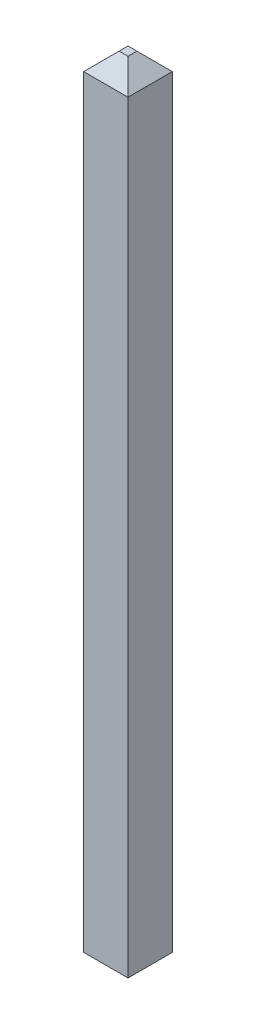
SolidWorks part; units mm, degrees
ref_plane "Front Plane" through (0, 0, 0) normal (0, 0, 1) x (1, 0, 0)
ref_plane "Top Plane" through (0, 0, 0) normal (0, 1, 0) x (1, 0, 0)
ref_plane "Right Plane" through (0, 0, 0) normal (1, 0, 0) x (0, 0, -1)
sketch "Sketch1" plane through (0, 0, 0) normal (0, 1, 0) x (1, 0, 0)
  line L0 (-0.3175, 0.3175) -> (0.3175, -0.3175) construction
  line L1 (-0.3175, 0.3175) -> (0.3175, 0.3175)
  line L2 (-0.3175, 0.3175) -> (-0.3175, -0.3175)
  line L3 (-0.3175, -0.3175) -> (0.3175, -0.3175)
  line L4 (0.3175, 0.3175) -> (0.3175, -0.3175)
  point P4 (0, 0)
  dimension "D1" = 0.635
  dimension "D2" = 0.635
extrude "Boss-Extrude1" add sketch "Sketch1" along normal blind 11.43
chamfer "Chamfer1" distance 0.254 angle 45 4 edges at (0, 11.43, -0.3175) (0.3175, 11.43, 0) (0, 11.43, 0.3175) (-0.3175, 11.43, 0)
chamfer "Chamfer2" distance 0.254 angle 45 4 edges at (-0.3175, 0, 0) (0, 0, -0.3175) (0.3175, 0, 0) (0, 0, 0.3175)
